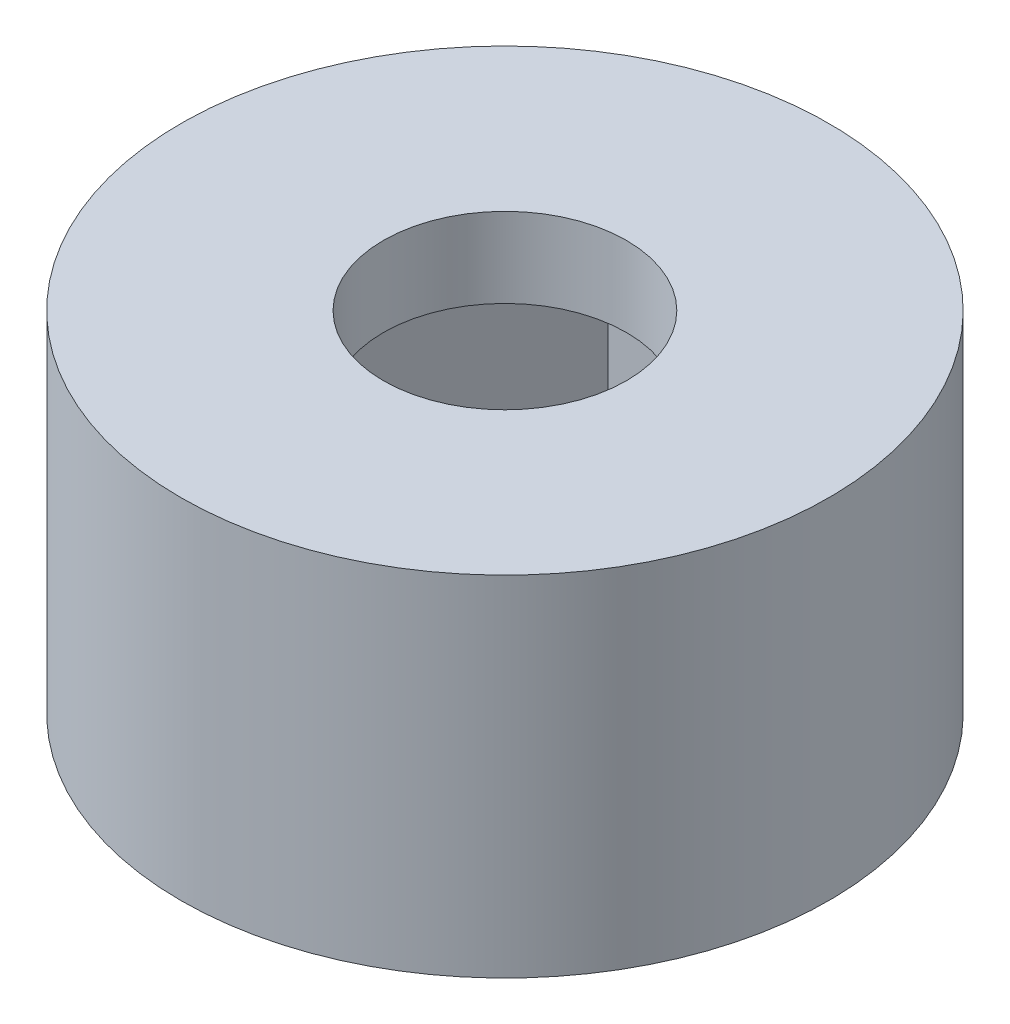
SolidWorks part; units mm, degrees
ref_plane "Front" through (0, 0, 0) normal (0, 0, 1) x (1, 0, 0)
ref_plane "Top" through (0, 0, 0) normal (0, 1, 0) x (1, 0, 0)
ref_plane "Right" through (0, 0, 0) normal (1, 0, 0) x (0, 0, -1)
sketch "Sketch1" plane through (0, 0, 0) normal (0, 1, 0) x (1, 0, 0)
  circle A0 centre (0, 0) radius 3.25
  dimension "D1" = 6.5
extrude "Boss-Extrude1" add sketch "Sketch1" along normal mid plane 3.5
sketch "Sketch2" plane through (0, 0, 0) normal (0, 1, 0) x (1, 0, 0)
  line L1 (2.829, 0) -> (1.4145, 2.45)
  line L2 (1.4145, 2.45) -> (-1.4145, 2.45)
  line L3 (-1.4145, 2.45) -> (-2.829, 0)
  line L4 (-2.829, 0) -> (-1.4145, -2.45)
  line L5 (-1.4145, -2.45) -> (1.4145, -2.45)
  line L6 (1.4145, -2.45) -> (2.829, 0)
  circle A0 centre (0, 0) radius 2.45 construction
  dimension "D1" = 4.9
extrude "Cut-Extrude1" cut sketch "Sketch2" against normal mid plane 1.9
hole_wizard "#2 Clearance Hole1" positions "Sketch3" profile "Sketch4" hole size "#2" standard "ANSI Inch" end condition through all
sketch "Sketch3" plane through (0, 1.75, 0) normal (0, 1, 0) x (1, 0, 0)
  point P0 (0, 0)
sketch "Sketch4" plane through (0, 1.75, 0) normal (1, 0, 0) x (0, 0, 1)
  line L0 (0, 0) -> (0, 3.5)
  line L1 (0, 3.5) -> (1.2192, 3.5)
  line L2 (1.2192, 3.5) -> (1.2192, 0)
  line L5 (1.2192, 0) -> (0, 0)
  line L11 (0, -6.35) -> (0, 107.95) construction
  dimension "Thru Hole Dia." = 2.4384
  dimension "Thru Hole Depth" = 3.5
